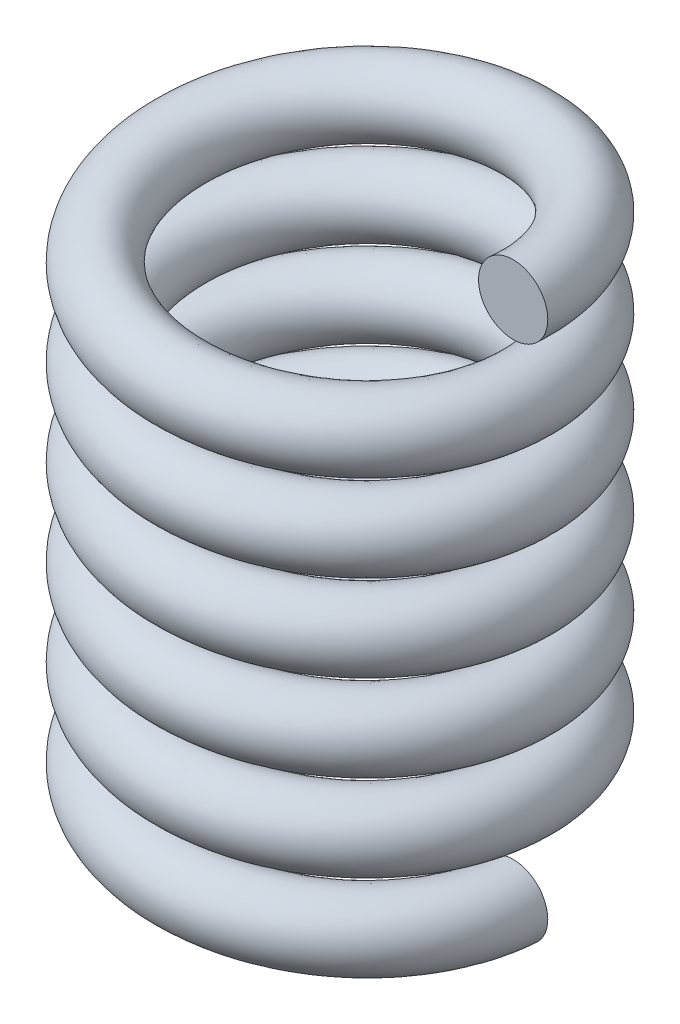
SolidWorks part; units mm, degrees
ref_plane "前基準面" through (0, 0, 0) normal (0, 0, 1) x (1, 0, 0)
ref_plane "上基準面" through (0, 0, 0) normal (0, 1, 0) x (1, 0, 0)
ref_plane "右基準面" through (0, 0, 0) normal (1, 0, 0) x (0, 0, -1)
sketch "草圖1" plane through (0, 0, 0) normal (0, 1, 0) x (1, 0, 0)
  circle A0 centre (0, 0) radius 10
curve "螺旋曲線/渦捲線1" pitch 5 height 30 turns 6
sketch "草圖2" plane through (0, 0, 0) normal (0, 0, 1) x (1, 0, 0)
  circle A0 centre (10, 0) radius 2
sweep "掃出1" add profiles "草圖2" path "螺旋曲線/渦捲線1"
